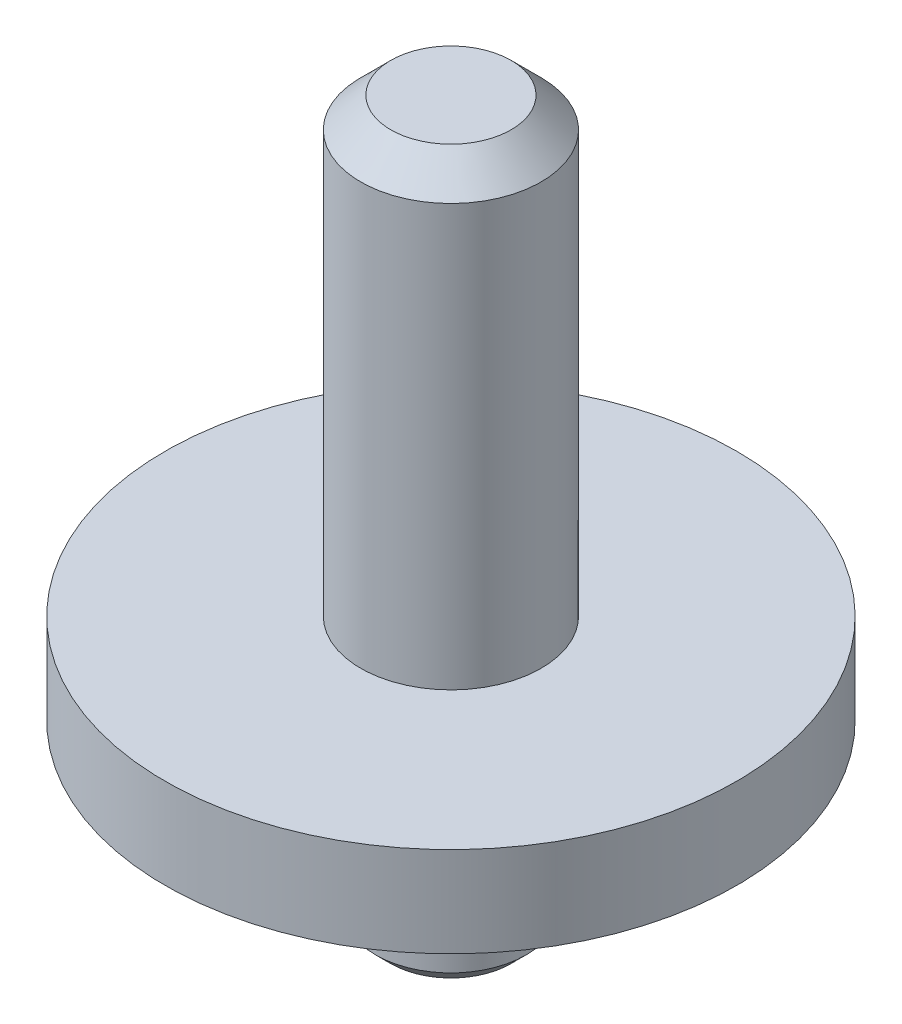
SolidWorks part; units mm, degrees
ref_plane "Front Plane" through (0, 0, 0) normal (0, 0, 1) x (1, 0, 0)
ref_plane "Top Plane" through (0, 0, 0) normal (0, 1, 0) x (1, 0, 0)
ref_plane "Right Plane" through (0, 0, 0) normal (1, 0, 0) x (0, 0, -1)
sketch "Sketch1" plane through (0, 0, 0) normal (0, 0, 1) x (1, 0, 0)
  line L0 (0, 0) -> (0, 27.7919) construction
  line L1 (0, 41.726) -> (-6, 41.726)
  line L2 (-6, 41.726) -> (-6, 11.726)
  line L3 (-6, 11.726) -> (-19, 11.726)
  line L4 (-19, 11.726) -> (-19, 5.726)
  line L5 (-19, 5.726) -> (-15, 5.726)
  line L6 (-15, 5.726) -> (-15, 8.726)
  line L7 (-15, 8.726) -> (-5, 8.726)
  line L8 (-5, 8.726) -> (-5, -6.274)
  line L9 (-5, -6.274) -> (0, -6.274)
  line L10 (0, -6.274) -> (0, 41.726)
  dimension "D1" = 12
  dimension "D2" = 30
  dimension "D3" = 38
  dimension "D4" = 3
  dimension "D5" = 3
  dimension "D6" = 30
  dimension "D7" = 15
  dimension "D8" = 10
revolve "Revolve1" add sketch "Sketch1" angle 360 about L0
chamfer "Chamfer1" distance 1 angle 45 1 edges at (0, -6.274, -5)
chamfer "Chamfer2" distance 2 angle 45 1 edges at (0, 41.726, -6)
